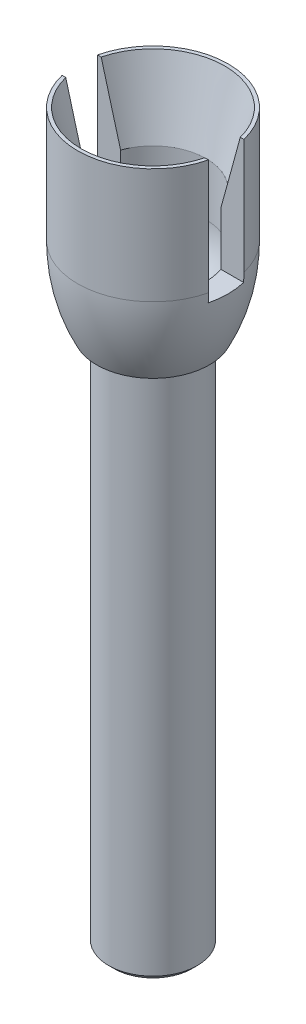
SolidWorks part; units mm, degrees
ref_plane "Plan de face" through (0, 0, 0) normal (0, 0, 1) x (1, 0, 0)
ref_plane "Plan de dessus" through (0, 0, 0) normal (0, 1, 0) x (1, 0, 0)
ref_plane "Plan de droite" through (0, 0, 0) normal (1, 0, 0) x (0, 0, -1)
sketch "Esquisse1" plane through (0, 0, 0) normal (0, 0, 1) x (1, 0, 0)
  line L0 (0, -1.2926) -> (0, 32.8235) construction
  line L1 (0, 0) -> (-2.2, 0)
  line L4 (-4.25, 34.5) -> (-4.25, 41)
  line L5 (-4.25, 41) -> (-4.05, 41)
  line L6 (-4.05, 41) -> (-3, 37)
  line L7 (-3, 37) -> (-3, 34)
  line L8 (0, 0) -> (0, 31)
  line L11 (-2.5, 30) -> (-3.1803, 30)
  line L12 (-2.5, 0.3) -> (-2.5, 30)
  line L13 (-2.2, 0) -> (-2.5, 0.3)
  arc A0 (-3, 34) -> (0, 31) centre (0, 34) ccw
  arc A1 (-3.1803, 30) -> (-4.25, 34.5) centre (5.75, 34.5) cw
  point P17 (-2.5, 0)
  dimension "D4" = 3
  dimension "D8" = 10
  dimension "D2" = 4
  dimension "D3" = 7
  dimension "D5" = 4
  dimension "D6" = 8.5
  dimension "D7" = 0.2
  dimension "D9" = 4.5
  dimension "D11" = 5
  dimension "D12" = 30
revolve "Révolution1" add sketch "Esquisse1" angle 360 about L0
sketch "Esquisse2" plane through (0, 0, 0) normal (1, 0, 0) x (0, 0, -1)
  line L0 (4.05, 41) -> (-4.05, 41) construction
  line L1 (-1, 34) -> (1, 34)
  line L2 (-1, 34) -> (-1, 41)
  line L3 (-1, 41) -> (1, 41)
  line L4 (1, 34) -> (1, 41)
  line L5 (-1, 34) -> (1, 41) construction
  line L6 (-1, 41) -> (1, 34) construction
  point P0 (0, 37.5)
  dimension "D1" = 2
  dimension "D2" = 7
extrude "Enlèv. mat.-Extru.1" cut sketch "Esquisse2" against normal up to next and the other way up to next
